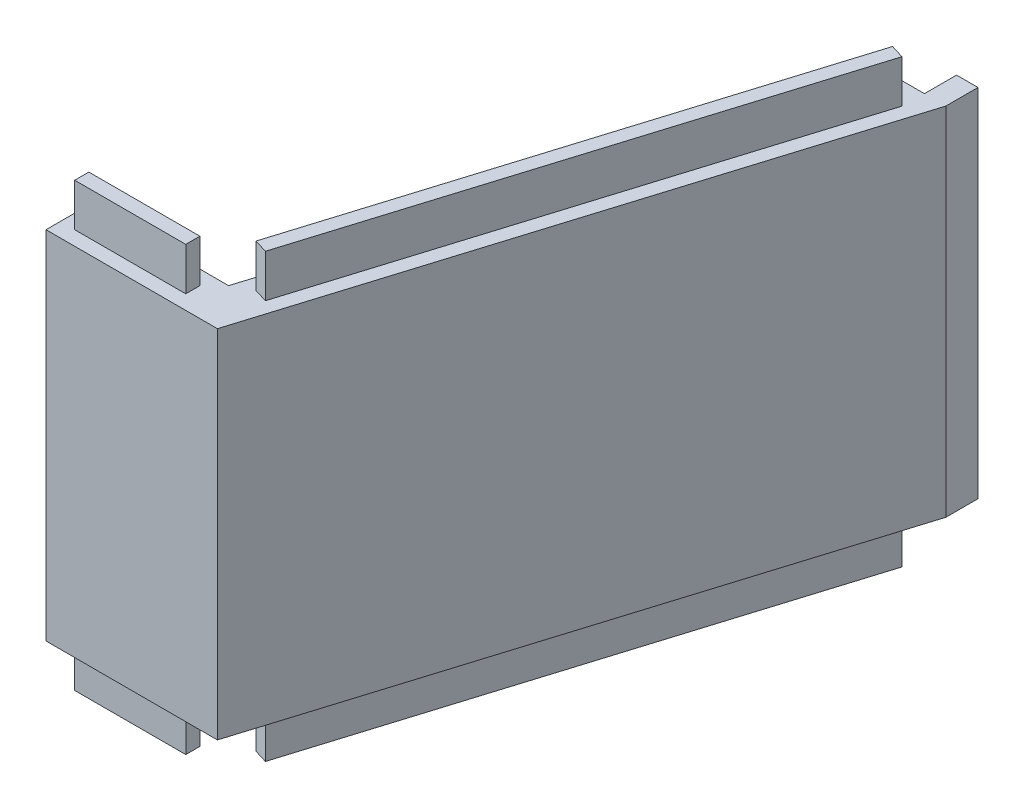
SolidWorks part; units mm, degrees
ref_plane "Front Plane" through (0, 0, 0) normal (1, 0, 0) x (0, 1, 0)
ref_plane "Top Plane" through (0, 0, 0) normal (0, 0, 1) x (0, 1, 0)
ref_plane "Right Plane" through (0, 0, 0) normal (0, 1, 0) x (-1, 0, 0)
sketch "Sketch1" plane through (0, 0, 0) normal (0, 1, 0) x (-1, 0, 0)
  line L0 (-10.3119, 17.5706) -> (29.6881, 147.5706)
  line L1 (-10.3119, 10.0706) -> (-5.3119, 10.0706)
  line L2 (-10.3119, 10.0706) -> (-10.3119, 17.5706)
  line L3 (-10.3119, 17.5706) -> (-5.3119, 17.5706)
  line L4 (-5.3119, 10.0706) -> (-5.3119, 17.5706)
  line L13 (-10.3119, 17.5706) -> (29.6881, 147.5706)
  line L14 (-10.3119, 17.5706) -> (-0.7541, 14.6298)
  line L15 (-10.3119, 17.5706) -> (69.6881, 17.5706) construction
  line L16 (-10.3119, 17.5706) -> (-10.3119, 137.5706) construction
  line L17 (-10.3119, 137.5706) -> (69.6881, 137.5706) construction
  line L18 (69.6881, 17.5706) -> (69.6881, 137.5706) construction
  line L19 (69.6881, 137.5706) -> (29.6881, 137.5706)
  line L20 (69.6881, 137.5706) -> (69.6881, 147.5706)
  line L21 (69.6881, 147.5706) -> (29.6881, 147.5706)
  line L22 (29.6881, 137.5706) -> (29.6881, 147.5706)
  line L23 (29.6881, 147.5706) -> (39.2459, 144.6298)
  line L24 (-0.7541, 14.6298) -> (39.2459, 144.6298)
  line L25 (-5.3119, 17.5706) -> (0.1508, 17.5706)
  dimension "D1" = 7.5
  dimension "D2" = 5
  dimension "D3" = 120
  dimension "D4" = 80
  dimension "D5" = 10
  dimension "D6" = 40
  dimension "D7" = 10
extrude "Boss-Extrude1" add sketch "Sketch1" along normal blind 83.125 contours L24 L19 L20 L21 L23 | L19 L24 L23 L22 | L3 L25 L24 L19 L22 L0 | L14 L2 L1 L4 | L3 L14 L4
sketch "Sketch2" plane through (0, 83.125, 0) normal (0, 1, 0) x (-1, 0, 0)
  line L0 (37.0738, 137.5706) -> (0.1508, 17.5706)
  line L1 (37.0738, 137.5706) -> (69.6881, 137.5706)
  line L2 (37.0738, 137.5706) -> (37.0738, 147.5706)
  line L3 (37.0738, 147.5706) -> (69.6881, 147.5706)
  line L4 (69.6881, 137.5706) -> (69.6881, 147.5706)
  line L5 (37.0738, 137.5706) -> (27.5161, 140.5115)
  line L6 (0.1508, 17.5706) -> (-9.407, 20.5115)
  line L7 (27.5161, 140.5115) -> (-9.407, 20.5115)
  line L9 (32.8868, 135.3539) -> (-2.0659, 21.7577)
  line L10 (-2.0659, 21.7577) -> (-5.22, 22.7281)
  line L11 (29.7327, 136.3244) -> (-5.22, 22.7281)
  line L12 (32.8868, 135.3539) -> (29.7327, 136.3244)
  line L13 (40.4238, 140.9206) -> (40.4238, 144.2206)
  line L14 (40.4238, 144.2206) -> (66.3381, 144.2206)
  line L15 (66.3381, 140.9206) -> (66.3381, 144.2206)
  line L16 (40.4238, 140.9206) -> (66.3381, 140.9206)
  line L17 (69.6881, 137.5706) -> (69.6881, 147.5706) construction
  line L18 (29.7327, 136.3244) -> (33.1931, 147.5706)
  line L20 (32.8868, 135.3539) -> (36.6458, 147.5706)
  line L21 (36.6458, 147.5706) -> (33.1931, 147.5706)
  line L22 (40.4238, 144.2206) -> (32.1623, 144.2206)
  line L23 (32.1623, 144.2206) -> (31.1469, 140.9206)
  line L24 (31.1469, 140.9206) -> (40.4238, 140.9206)
  line L25 (-10.3119, 17.5706) -> (29.6881, 147.5706) construction
  dimension "D1" = 3.35
extrude "Boss-Extrude2" add sketch "Sketch2" along normal blind 10 contours L9 L12 L11 L10 | L13 L16 L15 L14
ref_plane "Plane1" through (0, 41.5625, 0) normal (0, 1, 0) x (1, 0, 0)
mirror "Mirror1" about plane through (0, 41.5625, 0) normal (0, 1, 0) of "Boss-Extrude2"
sketch "Sketch3" plane through (0, 83.125, 0) normal (0, 1, 0) x (-1, 0, 0)
  line L1 (6.3046, 37.5706) -> (69.6881, 37.5706) construction
  line L2 (6.3046, 37.5706) -> (6.3046, 137.5706) construction
  line L3 (6.3046, 137.5706) -> (69.6881, 137.5706) construction
  line L4 (69.6881, 37.5706) -> (69.6881, 137.5706) construction
  line L5 (69.6881, 37.5706) -> (6.3046, 37.5706)
  line L6 (69.6881, 37.5706) -> (69.6881, 42.5706)
  line L7 (69.6881, 42.5706) -> (6.3046, 42.5706)
  line L8 (6.3046, 37.5706) -> (6.3046, 42.5706)
  line L9 (0.1508, 17.5706) -> (37.0738, 137.5706) construction
  line L10 (57.1881, 37.5706) -> (59.6881, 37.5706)
  line L11 (57.1881, 37.5706) -> (57.1881, 27.5706)
  line L12 (57.1881, 27.5706) -> (59.6881, 27.5706)
  line L13 (59.6881, 37.5706) -> (59.6881, 27.5706)
  line L14 (34.6881, 37.5706) -> (37.1881, 37.5706)
  line L15 (34.6881, 37.5706) -> (34.6881, 27.5706)
  line L16 (34.6881, 27.5706) -> (37.1881, 27.5706)
  line L17 (37.1881, 37.5706) -> (37.1881, 27.5706)
  line L18 (12.1881, 37.5706) -> (14.6881, 37.5706)
  line L19 (12.1881, 37.5706) -> (12.1881, 27.5706)
  line L20 (12.1881, 27.5706) -> (14.6881, 27.5706)
  line L21 (14.6881, 37.5706) -> (14.6881, 27.5706)
  line L22 (57.1881, 27.5706) -> (37.1881, 27.5706)
  line L23 (57.1881, 27.5706) -> (57.1881, 37.5706)
  line L24 (57.1881, 37.5706) -> (37.1881, 37.5706)
  line L25 (37.1881, 27.5706) -> (37.1881, 37.5706)
  line L26 (57.1881, 27.5706) -> (37.1881, 37.5706) construction
  line L27 (57.1881, 37.5706) -> (37.1881, 27.5706) construction
  line L28 (34.6881, 27.5706) -> (14.6881, 27.5706)
  line L29 (34.6881, 27.5706) -> (34.6881, 37.5706)
  line L30 (34.6881, 37.5706) -> (14.6881, 37.5706)
  line L31 (14.6881, 27.5706) -> (14.6881, 37.5706)
  line L32 (34.6881, 27.5706) -> (14.6881, 37.5706) construction
  line L33 (34.6881, 37.5706) -> (14.6881, 27.5706) construction
  line L34 (0.1508, 17.5706) -> (6.3046, 17.5706) construction
  line L35 (0.1508, 17.5706) -> (0.1508, 37.5706) construction
  line L36 (0.1508, 37.5706) -> (6.3046, 37.5706) construction
  line L37 (6.3046, 17.5706) -> (6.3046, 37.5706) construction
  line L38 (0.1508, 17.5706) -> (6.3046, 37.5706) construction
  line L39 (0.1508, 37.5706) -> (6.3046, 17.5706) construction
  point P20 (69.6881, 40.0706)
  point P21 (6.3046, 40.0706)
  point P24 (47.1881, 32.5706)
  point P25 (24.6881, 32.5706)
  point P29 (3.2277, 27.5706)
  line M17 (0.1508, 17.5706) -> (37.0738, 137.5706)
  dimension "D2" = 5
  dimension "D1" = 63.3835
  dimension "D3" = 2.5
  dimension "D4" = 2.5
  dimension "D5" = 2.5
  dimension "D6" = 10
  dimension "D7" = 20
  dimension "D8" = 20
  dimension "D9" = 5.8835
  dimension "D10" = 10
  dimension "D11" = 20
extrude "Boss-Extrude3" [suppressed] add sketch "Sketch3" against normal blind 176 contours L6 L7 L5 M17 | L21 L5 L19 L20 | L17 L5 L15 L16 | L13 L5 L11 L12
sketch "Sketch4" [suppressed] plane through (-14.6881, 0, 0) normal (-1, 0, 0) x (0, -1, 0)
  line L1 (-83.125, 27.5706) -> (-77.625, 27.5706) construction
  line L2 (-83.125, 27.5706) -> (-83.125, 31.6956) construction
  line L3 (-83.125, 31.6956) -> (-77.625, 31.6956) construction
  line L4 (-77.625, 27.5706) -> (-77.625, 31.6956) construction
  circle A0 centre (-77.625, 31.6956) radius 1.9
  circle A1 centre (79.2, 31.6956) radius 1.9
  dimension "D3" = 3.8
  dimension "D1" = 5.5
  dimension "D2" = 4.125
  dimension "D5" = 156.825
  dimension "D4" = 2
extrude "Cut-Extrude2" [suppressed] cut sketch "Sketch4" against normal up to next
sketch "Sketch5" [suppressed] plane through (-37.1881, 0, 0) normal (-1, 0, 0) x (0, -1, 0)
  line L1 (-83.125, 27.5706) -> (-72.625, 27.5706) construction
  line L2 (-83.125, 27.5706) -> (-83.125, 31.6956) construction
  line L3 (-83.125, 31.6956) -> (-72.625, 31.6956) construction
  line L4 (-72.625, 27.5706) -> (-72.625, 31.6956) construction
  circle A0 centre (-72.625, 31.6956) radius 1.9
  circle A3 centre (84.2, 31.6956) radius 1.9
  dimension "D3" = 3.8
  dimension "D5" = 156.825
  dimension "D4" = 2
  dimension "D1" = 4.125
  dimension "D2" = 10.5
extrude "Cut-Extrude3" [suppressed] cut sketch "Sketch5" against normal up to next
sketch "Sketch6" [suppressed] plane through (-59.6881, 0, 0) normal (-1, 0, 0) x (0, -1, 0)
  line L0 (-83.125, 17.5706) -> (-83.125, 37.5706) construction
  line L1 (-83.125, 27.5706) -> (-67.625, 27.5706) construction
  line L2 (-83.125, 27.5706) -> (-83.125, 31.4206) construction
  line L3 (-83.125, 31.4206) -> (-67.625, 31.4206) construction
  line L4 (-67.625, 27.5706) -> (-67.625, 31.4206) construction
  circle A0 centre (-67.625, 31.4206) radius 1.9
  circle A1 centre (44.965, 31.4206) radius 1.9
  dimension "D3" = 3.8
  dimension "D4" = 2
  dimension "D1" = 3.85
  dimension "D2" = 15.5
extrude "Cut-Extrude4" [suppressed] cut sketch "Sketch6" against normal up to next
sketch "Sketch7" plane through (0, 83.125, 0) normal (0, 1, 0) x (-1, 0, 0)
  line L1 (37.0738, 137.5706) -> (69.6881, 137.5706) construction
  line L2 (37.0738, 137.5706) -> (37.0738, 127.5706) construction
  line L3 (37.0738, 127.5706) -> (69.6881, 127.5706) construction
  line L4 (69.6881, 137.5706) -> (69.6881, 127.5706) construction
  point P5 (69.6881, 137.5706)
  point P7 (69.6881, 128.6088)
  dimension "D1" = 10
equation "\"whitekey_cutout_length\"= 101.5"
equation "\"key_mount_recess_length\"=50"
equation "\"key_mount_recess_height\"=12.5"
equation "\"key_mount_recess_depth\"=1.5"
equation "\"wall_thickness\"=10"
equation "\"guide_brace_height\"=20"
equation "\"guide_brace_thickness\"=2"
equation "\"dowel_recess_depth\"=10"
equation "\"dowel_recess_offset\"=3.25"
equation "\"dowel_insert_tolerance\"=0.1"
equation "\"base_mount_height\"=40"
equation "\"base_rear_length\"=80"
equation "\"base_front_length\"=111.5"
equation "\"screw_hole_wall_offset\"=7.25"
equation "\"screw_hole_edge_inset\"=\"dowel_recess_depth\"/2"
equation "\"screw_hole_diameter\"=3.8"
equation "\"screw_head_hole_diameter\"=6.7"
equation "\"screw_nut_hole_side_len\"=3.5"
equation "\"screw_nut_recess_offset\"=0.35"
equation "\"screw_head_and_nut_recess_depth\"=2.5"
equation "\"screw_shaft_diameter\"=3.5"
equation "\"switch_board_width\"=30"
equation "\"switch_board_thickness\"=1.6"
equation "\"switch_board_wall_offset\"=11.5"
equation "\"heatset_insert_hole_diameter\"=4.8"
equation "\"heatset_insert_hole_depth\"=3.8"
equation "\"front_rear_panel_width\"=23.75"
equation "\"front_panel_height\"=24"
equation "\"front_rear_panel_recess_depth\"=5"
equation "\"rod_diameter\"=5"
equation "\"rod_head_diameter\"=8"
equation "\"rod_length_adj\"=0.5"
equation "\"rod_insert_length\"=2.8"
equation "\"switch_black_key_mount_height\"=8"
equation "\"switch_white_key_mount_height\"=3"
equation "\"D7@Sketch1\"=\"wall_thickness\""
equation "\"D5@Sketch1\"=\"wall_thickness\""
equation "\"D2@Sketch1\"=\"wall_thickness\"/2"
equation "\"D4@Sketch1\"=\"base_rear_length\""
equation "\"D3@Sketch1\"=\"base_mount_height\"*3"
equation "\"D1@Sketch1\"=\"wall_thickness\"*0.75"
equation "\"D1@Boss-Extrude1\"=\"front_rear_panel_width\"*3.5"
equation "\"D1@Sketch2\"=\"dowel_recess_offset\"+\"dowel_insert_tolerance\""
equation "\"D1@Boss-Extrude2\"=\"dowel_recess_depth\""
equation "\"D2@Sketch3\"=\"wall_thickness\"/2"
equation "\"D3@Sketch3\"=\"wall_thickness\"/4"
equation "\"D4@Sketch3\"=\"wall_thickness\"/4"
equation "\"D5@Sketch3\"=\"wall_thickness\"/4"
equation "\"D6@Sketch3\"=\"wall_thickness\""
equation "\"D7@Sketch3\"=\"wall_thickness\"*2"
equation "\"D8@Sketch3\"=\"wall_thickness\"*2"
equation "\"D10@Sketch3\"=\"wall_thickness\""
equation "\"D3@Sketch4\"=\"screw_hole_diameter\""
equation "\"D3@Sketch5\"=\"screw_hole_diameter\""
equation "\"D3@Sketch6\"=\"screw_hole_diameter\""
equation "\"D1@Sketch7\"=\"wall_thickness\""
